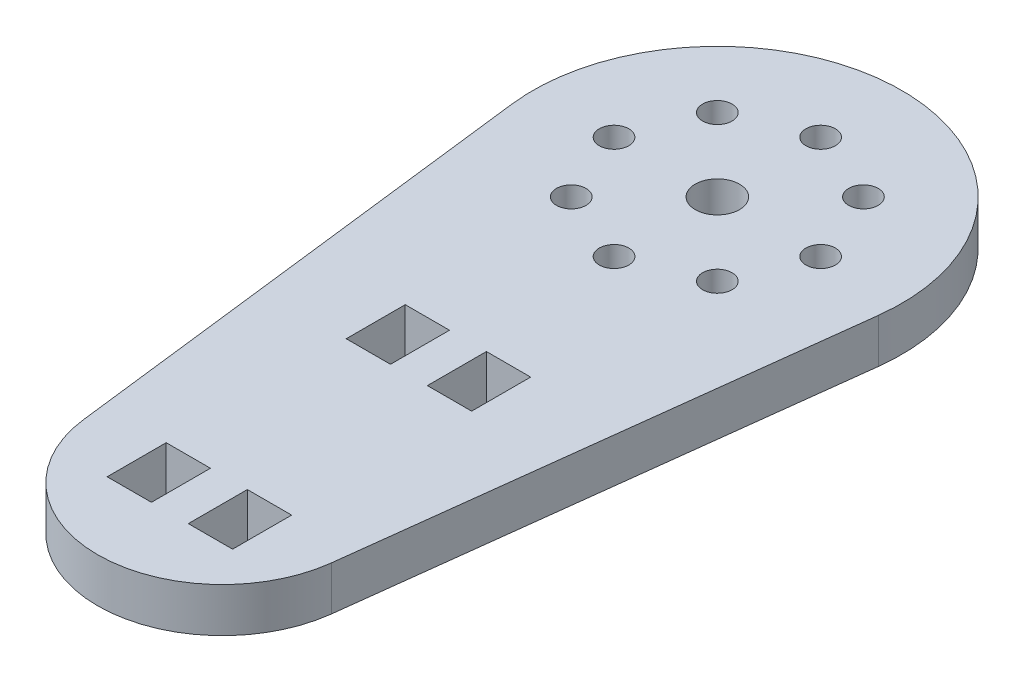
SolidWorks part; units mm, degrees
ref_plane "Front Plane" through (0, 0, 0) normal (0, 0, 1) x (1, 0, 0)
ref_plane "Top Plane" through (0, 0, 0) normal (0, 1, 0) x (1, 0, 0)
ref_plane "Right Plane" through (0, 0, 0) normal (1, 0, 0) x (0, 0, -1)
sketch "Sketch1" plane through (0, 0, 0) normal (0, 1, 0) x (1, 0, 0)
  line L0 (-7.5, -42) -> (-12.4092, -1.5043)
  line L1 (7.5, -42) -> (-7.5, -42)
  line L2 (7.5, -42) -> (7.5, -12)
  line L3 (7.5, -12) -> (-7.5, -12)
  line L4 (-7.5, -42) -> (-7.5, -12)
  line L5 (7.5, -42) -> (-7.5, -12) construction
  line L6 (7.5, -12) -> (-7.5, -42) construction
  line L7 (7.5, -42) -> (12.4092, -1.5043)
  line L8 (0, -27) -> (0, -12) construction
  line L9 (4.25, -16.9) -> (1.25, -16.9)
  line L10 (-4.25, -20.9) -> (-1.25, -20.9)
  line L11 (-4.25, -20.9) -> (-4.25, -16.9)
  line L12 (-4.25, -16.9) -> (-1.25, -16.9)
  line L13 (-1.25, -20.9) -> (-1.25, -16.9)
  line L14 (-4.25, -20.9) -> (-1.25, -16.9) construction
  line L15 (-4.25, -16.9) -> (-1.25, -20.9) construction
  line L16 (1.25, -20.9) -> (1.25, -16.9)
  line L17 (4.25, -20.9) -> (1.25, -20.9)
  line L18 (4.25, -20.9) -> (4.25, -16.9)
  line L19 (0, -27) -> (-7.5, -27) construction
  line L20 (4.25, -33.1) -> (4.25, -37.1)
  line L21 (4.25, -33.1) -> (1.25, -33.1)
  line L22 (1.25, -33.1) -> (1.25, -37.1)
  line L23 (4.25, -37.1) -> (1.25, -37.1)
  line L24 (-4.25, -37.1) -> (-1.25, -37.1)
  line L25 (-1.25, -33.1) -> (-1.25, -37.1)
  line L26 (-4.25, -33.1) -> (-1.25, -33.1)
  line L27 (-4.25, -33.1) -> (-4.25, -37.1)
  arc A0 (-1, -12.4599) -> (1, -12.4599) centre (0, 0) ccw
  circle A1 centre (0, 0) radius 1.5
  arc A4 (12.4092, -1.5043) -> (-12.4092, -1.5043) centre (0, 0) ccw
  point P3 (0, -27)
  point P17 (-2.75, -18.9)
  dimension "D2" = 3
  dimension "D3" = 25
  dimension "D5" = 3
  dimension "D1" = 15
  dimension "D4" = 27
  dimension "D9" = 4
  dimension "D10" = 1.25
  dimension "D11" = 6.1
  dimension "D12" = 30
extrude "Boss-Extrude2" add sketch "Sketch1" along normal blind 3
fillet "Fillet1" radius 8.4641 4 edges at (0, 3, 42) (0, 0, 42) (7.5, 1.5, 42) (-7.5, 1.5, 42)
sketch "Sketch2" plane through (0, 3, 0) normal (0, 1, 0) x (1, 0, 0)
  circle A0 centre (0, 7) radius 1
  circle A1 centre (4.9497, 4.9497) radius 1
  circle A2 centre (7, 0) radius 1
  circle A3 centre (4.9497, -4.9497) radius 1
  circle A4 centre (0, -7) radius 1
  circle A5 centre (-4.9497, -4.9497) radius 1
  circle A6 centre (-7, 0) radius 1
  circle A7 centre (-4.9497, 4.9497) radius 1
  dimension "D1" = 2
  dimension "D2" = 7
  dimension "D3" = 8
extrude "Cut-Extrude1" cut sketch "Sketch2" against normal up to surface (3 mm away) up to face at (0, 0, 16.3897)
